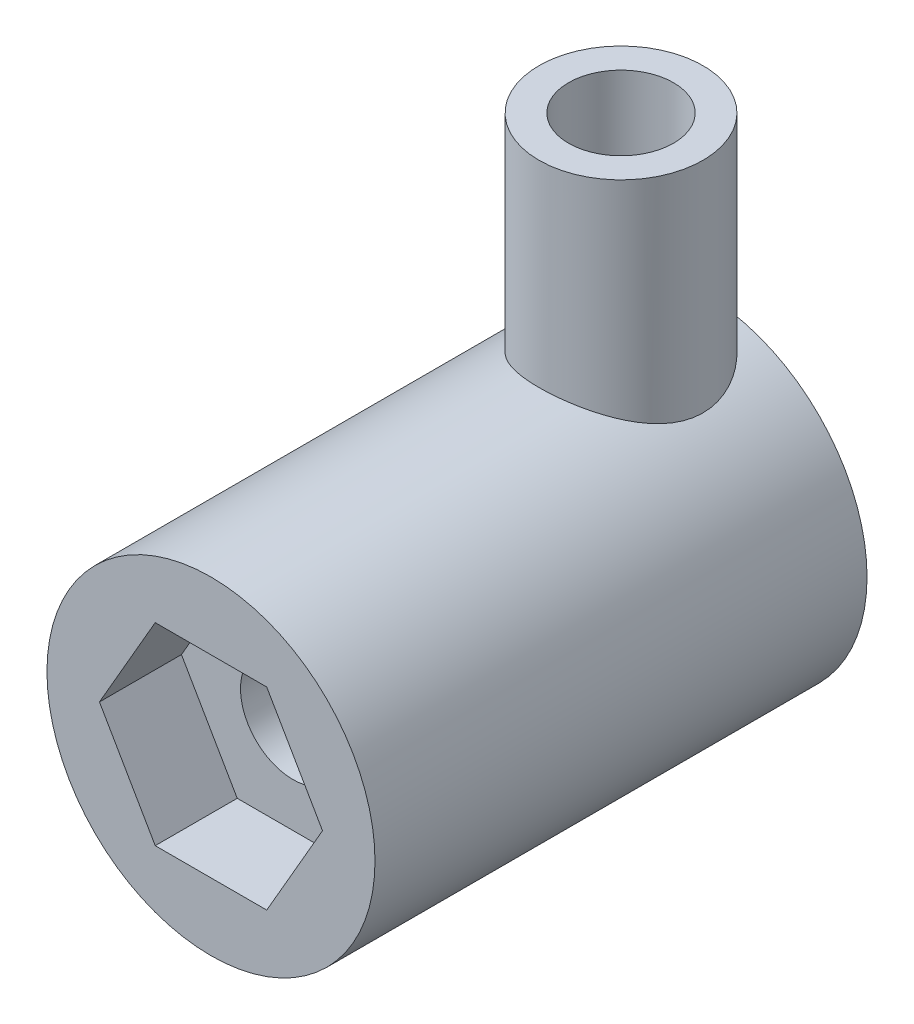
SolidWorks part; units mm, degrees
ref_plane "前视基准面" through (0, 0, 0) normal (0, 0, 1) x (1, 0, 0)
ref_plane "上视基准面" through (0, 0, 0) normal (0, 1, 0) x (1, 0, 0)
ref_plane "右视基准面" through (0, 0, 0) normal (1, 0, 0) x (0, 0, -1)
sketch "草图1" plane through (0, 0, 0) normal (0, 0, 1) x (1, 0, 0)
  circle A0 centre (0, 0) radius 5
  circle A1 centre (0, 0) radius 1.6
  dimension "D1" = 10
  dimension "D2" = 3.2
extrude "凸台-拉伸1" add sketch "草图1" along normal blind 15
sketch "草图2" plane through (0, 0, 15) normal (0, 0, 1) x (1, 0, 0)
  line L1 (3.4, 0) -> (1.7, 2.9445)
  line L2 (1.7, 2.9445) -> (-1.7, 2.9445)
  line L3 (-1.7, 2.9445) -> (-3.4, 0)
  line L4 (-3.4, 0) -> (-1.7, -2.9445)
  line L5 (-1.7, -2.9445) -> (1.7, -2.9445)
  line L6 (1.7, -2.9445) -> (3.4, 0)
  circle A0 centre (0, 0) radius 2.9445 construction
  dimension "D1" = 3.4
extrude "切除-拉伸1" cut sketch "草图2" against normal blind 2.5
ref_plane "基准面1" through (0, 4, 0) normal (0, 1, 0) x (1, 0, 0)
sketch "草图4" plane through (0, 4, 0) normal (0, 1, 0) x (1, 0, 0)
  line L0 (5, 0) -> (-5, 0) construction
  circle A0 centre (0, -2.5) radius 2.5
  circle A1 centre (0, -2.5) radius 1.6
  dimension "D1" = 5
  dimension "D3" = 3.2
  dimension "D2" = 2.5
extrude "凸台-拉伸2" add sketch "草图4" along normal blind 7
